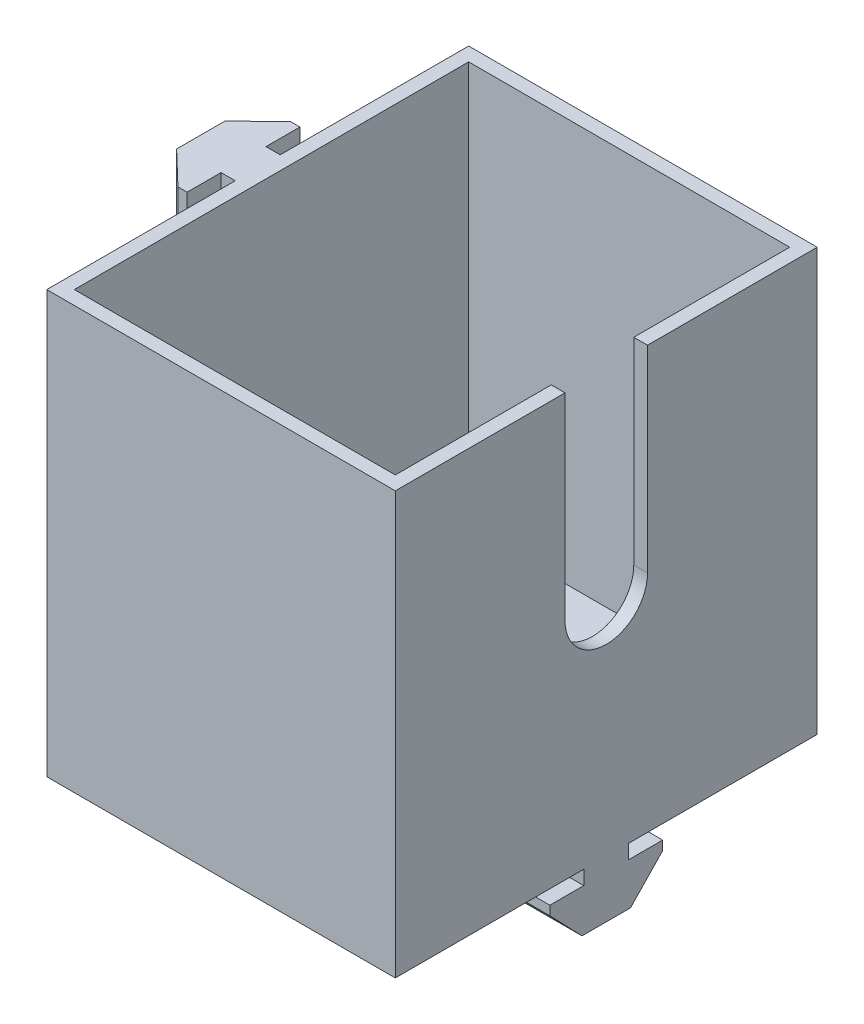
SolidWorks part; units mm, degrees
other "Marquage1"
sketch "Esquisse7" plane through (-22.1, 26.1, 52.2) normal (-0.1348, 0.2678, 0.954) x (-0.088, -0.9622, 0.2577)
ref_plane "Plan de face" through (0, 0, 0) normal (0, 0, 1) x (1, 0, 0)
ref_plane "Plan de dessus" through (0, 0, 0) normal (0, 1, 0) x (1, 0, 0)
ref_plane "Plan de droite" through (0, 0, 0) normal (1, 0, 0) x (0, 0, -1)
sketch "Esquisse1" plane through (0, 0, 0) normal (0, 0, 1) x (1, 0, 0)
  line L1 (-22.1, 26.1) -> (22.1, 26.1)
  line L2 (-22.1, 26.1) -> (-22.1, -26.1)
  line L3 (-22.1, -26.1) -> (22.1, -26.1)
  line L4 (22.1, 26.1) -> (22.1, -26.1)
  line L5 (-22.1, 26.1) -> (22.1, -26.1) construction
  line L6 (-22.1, -26.1) -> (22.1, 26.1) construction
  point P0 (0, 0)
  dimension "D1" = 44.2
  dimension "D2" = 52.2
extrude "Boss.-Extru.1" add sketch "Esquisse1" along normal blind 52.2
sketch "Esquisse2" plane through (22.1, 0, 0) normal (1, 0, 0) x (0, 0, -1)
  line L0 (-52.2, -19.9) -> (-28.55, -19.9)
  line L1 (-52.2, -26.1) -> (-52.2, 26.1) construction
  line L2 (-28.55, -19.9) -> (-28.55, -21.45)
  line L3 (-28.55, -21.45) -> (-32.25, -21.45)
  line L4 (-32.25, -21.45) -> (-32.25, -22.45)
  line L5 (-32.25, -22.45) -> (-28.7456, -26.1)
  line L6 (-52.2, -26.1) -> (0, -26.1) construction
  point P4 (0, 0)
  point P11 (-29.41, -26.1)
  dimension "D1" = 23.65
  dimension "D2" = 6.2
  dimension "D3" = 1.55
  dimension "D4" = 3.7
  dimension "D5" = 1
  dimension "D6" = 5.06
extrude "Enlèv. mat.-Extru.2" cut sketch "Esquisse2" against normal blind 44.2 and the other way through all flip side to cut
sketch "Esquisse3" plane through (22.1, 0, 0) normal (1, 0, 0) x (0, 0, -1)
  line L0 (0, -19.9) -> (-23.65, -19.9)
  line L1 (0, -26.1) -> (0, 26.1) construction
  line L2 (-23.65, -19.9) -> (-23.65, -21.45)
  line L3 (-23.65, -21.45) -> (-19.95, -21.45)
  line L4 (-19.95, -21.45) -> (-19.95, -22.45)
  line L5 (-19.95, -22.45) -> (-23.4544, -26.1)
  line L6 (-28.7456, -26.1) -> (0, -26.1) construction
  dimension "D1" = 6.2
  dimension "D2" = 23.65
  dimension "D3" = 1.55
  dimension "D4" = 3.7
  dimension "D5" = 1
  dimension "D6" = 5.06
extrude "Enlèv. mat.-Extru.3" cut sketch "Esquisse3" against normal blind 44.2 and the other way through all
sketch "Esquisse4" plane through (0, 26.1, 0) normal (0, 1, 0) x (1, 0, 0)
  line L0 (-15.9, -52.2) -> (-15.9, -28.55)
  line L1 (22.1, -52.2) -> (-22.1, -52.2) construction
  line L2 (-15.9, -28.55) -> (-17.45, -28.55)
  line L3 (-17.45, -28.55) -> (-17.45, -32.25)
  line L4 (-17.45, -32.25) -> (-18.45, -32.25)
  line L5 (-18.45, -32.25) -> (-22.1, -28.7456)
  line L6 (-22.1, -52.2) -> (-22.1, 0) construction
  dimension "D1" = 6.2
  dimension "D2" = 23.65
  dimension "D3" = 1.55
  dimension "D4" = 3.7
  dimension "D5" = 1
  dimension "D6" = 5.06
extrude "Enlèv. mat.-Extru.4" cut sketch "Esquisse4" against normal blind 46 and the other way through all
sketch "Esquisse5" plane through (0, 26.1, 0) normal (0, 1, 0) x (1, 0, 0)
  line L0 (-15.9, 0) -> (-15.9, -23.65)
  line L1 (22.1, 0) -> (-22.1, 0) construction
  line L2 (-15.9, -23.65) -> (-17.45, -23.65)
  line L3 (-17.45, -23.65) -> (-17.45, -19.95)
  line L4 (-17.45, -19.95) -> (-18.45, -19.95)
  line L5 (-18.45, -19.95) -> (-22.1, -23.4544)
  line L6 (-22.1, -28.7456) -> (-22.1, 0) construction
  dimension "D1" = 6.2
  dimension "D2" = 23.65
  dimension "D3" = 1.55
  dimension "D4" = 3.7
  dimension "D5" = 1
  dimension "D6" = 5.06
extrude "Enlèv. mat.-Extru.5" cut sketch "Esquisse5" against normal blind 46 and the other way through all flip side to cut
sketch "Esquisse6" plane through (0, 0, 28.55) normal (0, 0, 1) x (1, 0, 0)
  line L0 (-22.1, -19.9) -> (-15.9, -19.9)
  line L1 (-15.9, -19.9) -> (-15.9, -26.0936)
extrude "Enlèv. mat.-Extru.7" cut sketch "Esquisse6" against normal through all both and the other way through all flip side to cut
sketch "Esquisse11" plane through (0, 26.1, 0) normal (0, 1, 0) x (1, 0, 0)
  line L0 (22.1, -52.2) -> (22.1, 0) construction
  line L1 (22.1, -49.1) -> (-15.9, -49.1)
  line L2 (-15.9, -28.55) -> (-15.9, -52.2) construction
  line L3 (22.1, -52.2) -> (-15.9, -52.2) construction
  dimension "D1" = 3.1
extrude "Enlèv. mat.-Extru.8" cut sketch "Esquisse11" against normal blind 46 and the other way through all
sketch "Esquisse12" plane through (0, 26.1, 0) normal (0, 1, 0) x (1, 0, 0)
  line L0 (22.1, -49.1) -> (22.1, 0) construction
  line L1 (22.1, -3.1) -> (-15.9, -3.1)
  line L2 (-15.9, -23.65) -> (-15.9, 0) construction
  line L3 (22.1, 0) -> (-15.9, 0) construction
  dimension "D1" = 3.1
extrude "Enlèv. mat.-Extru.9" cut sketch "Esquisse12" against normal blind 46 and the other way through all flip side to cut
sketch "Esquisse13" plane through (0, 26.1, 0) normal (0, 1, 0) x (1, 0, 0)
  line L0 (-14.4, -4.6) -> (-14.4, -47.6)
  line L1 (-14.4, -47.6) -> (20.6, -47.6)
  line L2 (20.6, -47.6) -> (20.6, -4.6)
  line L3 (20.6, -4.6) -> (-14.4, -4.6)
  line L5 (22.1, -49.1) -> (22.1, -3.1) construction
  line L6 (-15.9, -23.65) -> (-15.9, -3.1) construction
  line L7 (-15.9, -3.1) -> (22.1, -3.1) construction
  dimension "D1" = 35
  dimension "D2" = 43
  dimension "D3" = 1.5
  dimension "D4" = 1.5
  dimension "D5" = 1.5
extrude "Enlèv. mat.-Extru.10" cut sketch "Esquisse13" against normal blind 44
sketch "Esquisse14" plane through (22.1, 0, 0) normal (1, 0, 0) x (0, 0, -1)
  line L0 (-49.1, 26.1) -> (-3.1, 26.1) construction
  line L1 (-3.1, 26.1) -> (-21.6, 26.1)
  line L2 (-21.6, 26.1) -> (-21.6, 4.6)
  line L3 (-49.1, 26.1) -> (-30.6, 26.1)
  line L4 (-30.6, 26.1) -> (-30.6, 4.6)
  arc A0 (-21.6, 4.6) -> (-30.6, 4.6) centre (-26.1, 4.6) cw
  point P11 (0, 0)
  dimension "D5" = 4.5
  dimension "D1" = 18.5
  dimension "D2" = 18.5
  dimension "D3" = 21.5
  dimension "D4" = 21.5
extrude "Enlèv. mat.-Extru.11" cut sketch "Esquisse14" against normal blind 1.5 and the other way through all
